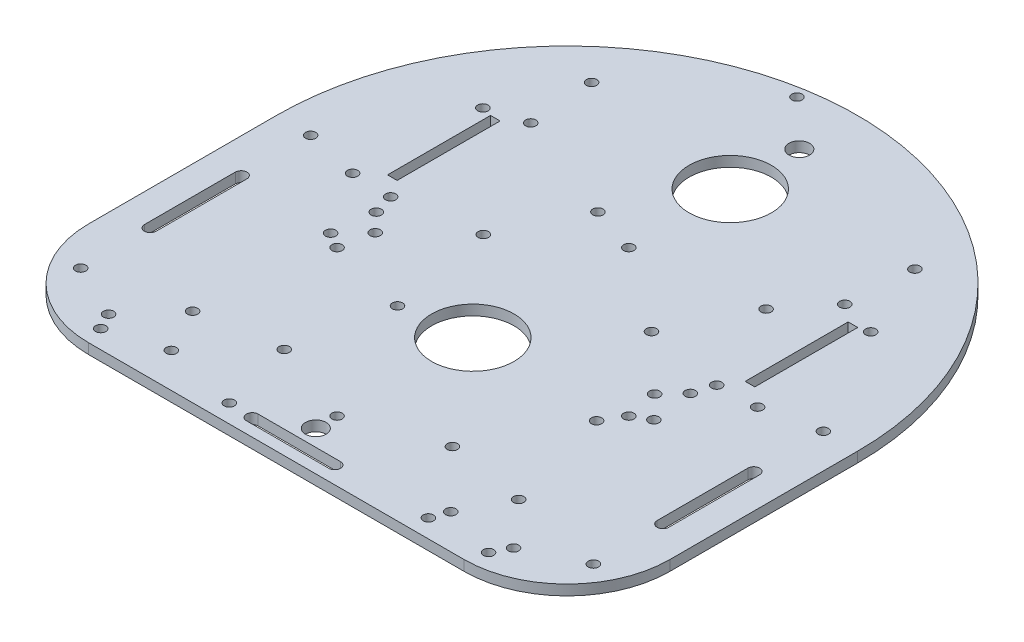
SolidWorks part; units mm, degrees
ref_plane "Front Plane" through (0, 0, 0) normal (0, 0, 1) x (1, 0, 0)
ref_plane "Top Plane" through (0, 0, 0) normal (0, 1, 0) x (1, 0, 0)
ref_plane "Right Plane" through (0, 0, 0) normal (1, 0, 0) x (0, 0, -1)
sketch "Sketch1" plane through (0, 0, 0) normal (0, 1, 0) x (1, 0, 0)
  line L3 (-139.4964, -88.8623) -> (-139.4964, -62.3877)
  line L79 (-78.5131, -120.1083) -> (-54.5131, -120.1083)
  line L85 (-15.8131, -40.9116) -> (-15.8131, -10.9116)
  line L86 (-117.2131, -10.9116) -> (-120.0131, -10.9116)
  line L87 (-121.1964, -126.8083) -> (-11.8298, -126.8083)
  line L88 (-142.8964, -88.8623) -> (-142.8964, -62.3877)
  line L89 (-78.5131, -123.5083) -> (-54.5131, -123.5083)
  line L90 (-13.0131, -40.9116) -> (-15.8131, -40.9116)
  line L91 (-13.0131, -10.9116) -> (-13.0131, -40.9116)
  line L92 (-15.8131, -10.9116) -> (-13.0131, -10.9116)
  line L93 (-120.0131, -10.9116) -> (-120.0131, -40.9116)
  line L94 (-120.0131, -40.9116) -> (-117.2131, -40.9116)
  line L95 (-117.2131, -40.9116) -> (-117.2131, -10.9116)
  line L96 (-151.1964, -42.125) -> (-151.1964, -96.8083)
  line L97 (18.1702, -96.8083) -> (18.1702, -42.125)
  line L98 (9.8702, -88.8623) -> (9.8702, -62.3877)
  line L99 (6.4702, -88.8623) -> (6.4702, -62.3877)
  circle A87 centre (-19.4171, 12.134) radius 1.5
  circle A89 centre (-19.4171, -63.9123) radius 1.5
  circle A90 centre (-113.6092, -63.9123) radius 1.5
  circle A91 centre (-113.6092, 12.134) radius 1.5
  circle A92 centre (-20.7631, -6.9416) radius 1.5
  circle A93 centre (-112.2631, -6.9416) radius 1.5
  circle A94 centre (-112.2631, -51.9416) radius 1.5
  circle A95 centre (-66.5131, -115.3083) radius 3
  circle A96 centre (8.1702, -42.125) radius 1.5
  circle A97 centre (-141.1964, -42.125) radius 1.5
  circle A98 centre (-66.5131, 5.4353) radius 12
  circle A99 centre (-66.5131, 25.5584) radius 3
  circle A100 centre (-66.5131, -69.5647) radius 12
  circle A101 centre (-107.2131, -116.6972) radius 1.5
  circle A102 centre (-25.8131, -116.6972) radius 1.5
  circle A103 centre (-25.8131, -57.2972) radius 1.5
  circle A104 centre (-123.0131, -10.1384) radius 1.5
  circle A105 centre (-107.2131, -57.2972) radius 1.5
  circle A106 centre (-114.0131, -46.0084) radius 1.5
  circle A107 centre (-19.0131, -46.0084) radius 1.5
  circle A108 centre (-19.0131, -103.7084) radius 1.5
  circle A109 centre (-114.0131, -103.7084) radius 1.5
  circle A110 centre (-10.0131, -10.1384) radius 1.5
  circle A111 centre (-10.0131, -121.4784) radius 1.5
  circle A112 centre (-123.0131, -121.4784) radius 1.5
  circle A113 centre (-125.5131, -116.6972) radius 1.5
  circle A114 centre (-125.5131, -45.5972) radius 1.5
  circle A115 centre (-7.5131, -116.6972) radius 1.5
  circle A116 centre (-7.5131, -45.5972) radius 1.5
  circle A117 centre (-80.0131, 38.3788) radius 1.5
  circle A118 centre (-80.0131, -19.6212) radius 1.5
  circle A119 centre (-31.0131, -19.6212) radius 1.5
  circle A120 centre (-27.5131, -72.5084) radius 1.5
  circle A121 centre (-27.5131, -121.5084) radius 1.5
  circle A122 centre (-85.5131, -72.5084) radius 1.5
  circle A123 centre (-85.5131, -121.5084) radius 1.5
  circle A124 centre (-42.0131, -100.0084) radius 1.5
  circle A125 centre (-91.0131, -100.0084) radius 1.5
  circle A126 centre (-42.0131, -42.0084) radius 1.5
  circle A127 centre (-91.0131, -42.0084) radius 1.5
  circle A128 centre (-66.5131, -109.125) radius 1.5
  circle A129 centre (-66.5131, -24.125) radius 1.5
  circle A130 centre (-24.0131, -66.625) radius 1.5
  circle A131 centre (-109.0131, -66.625) radius 1.5
  circle A132 centre (-141.1964, -109.125) radius 1.5
  circle A133 centre (8.1702, -109.125) radius 1.5
  circle A134 centre (-20.7631, -51.9416) radius 1.5
  arc A135 (6.4702, -88.8623) -> (9.8702, -88.8623) centre (8.1702, -88.8623) ccw
  arc A136 (-139.4964, -62.3877) -> (-142.8964, -62.3877) centre (-141.1964, -62.3877) ccw
  arc A137 (-142.8964, -88.8623) -> (-139.4964, -88.8623) centre (-141.1964, -88.8623) ccw
  arc A138 (-78.5131, -120.1083) -> (-78.5131, -123.5083) centre (-78.5131, -121.8083) ccw
  arc A139 (-54.5131, -123.5083) -> (-54.5131, -120.1083) centre (-54.5131, -121.8083) ccw
  arc A140 (-151.1964, -96.8083) -> (-121.1964, -126.8083) centre (-121.1964, -96.8083) ccw
  arc A141 (18.1702, -42.125) -> (-151.1964, -42.125) centre (-66.5131, -42.125) ccw
  arc A142 (-11.8298, -126.8083) -> (18.1702, -96.8083) centre (-11.8298, -96.8083) ccw
  arc A143 (9.8702, -62.3877) -> (6.4702, -62.3877) centre (8.1702, -62.3877) ccw
extrude "Boss-Extrude4" add sketch "Sketch1" along normal blind 3
